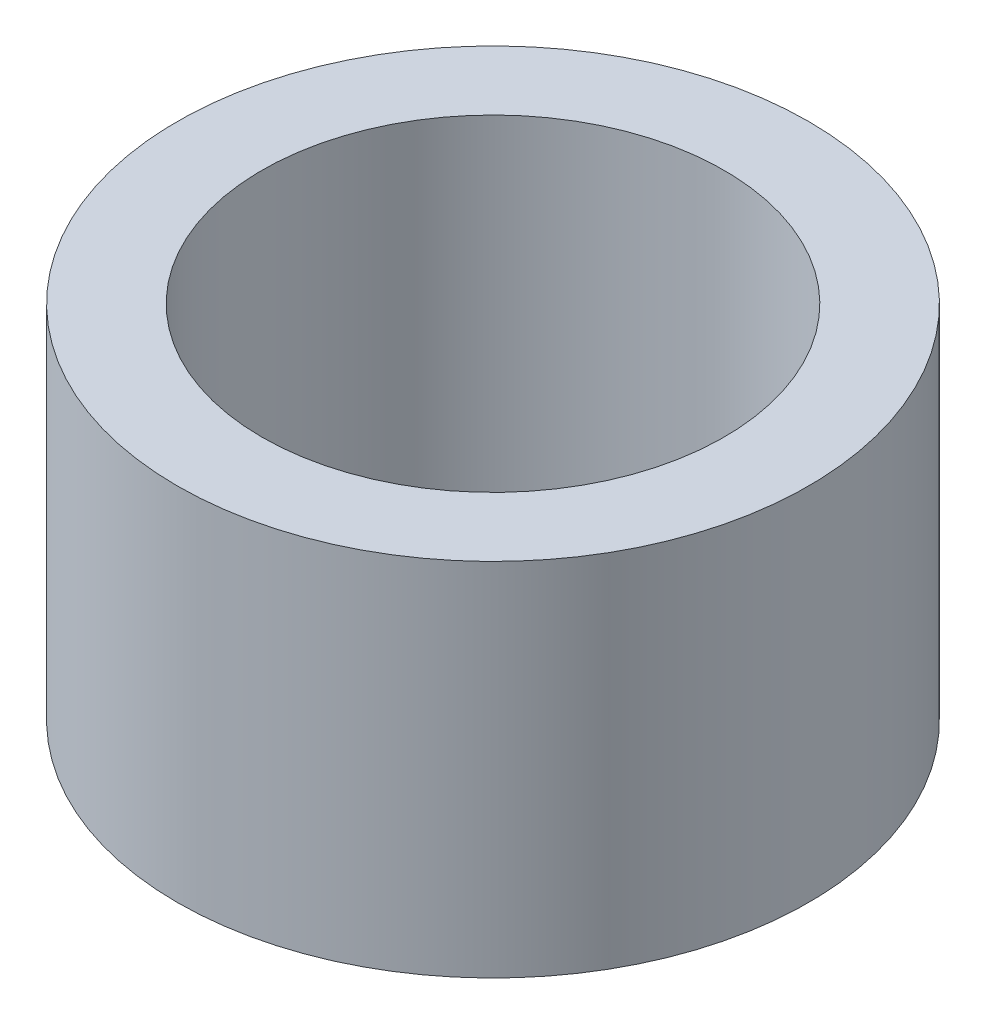
SolidWorks part; units mm, degrees
ref_plane "Ebene vorne" through (0, 0, 0) normal (0, 0, 1) x (1, 0, 0)
ref_plane "Ebene oben" through (0, 0, 0) normal (0, 1, 0) x (1, 0, 0)
ref_plane "Ebene rechts" through (0, 0, 0) normal (1, 0, 0) x (0, 0, -1)
sketch "Skizze1" plane through (0, 0, 0) normal (0, 1, 0) x (1, 0, 0)
  circle A0 centre (0, 0) radius 4.1
  circle A1 centre (0, 0) radius 5.6
  dimension "D1" = 8.2
  dimension "D2" = 11.2
extrude "Aufsatz-Linear austragen1" add sketch "Skizze1" along normal blind 6.4
